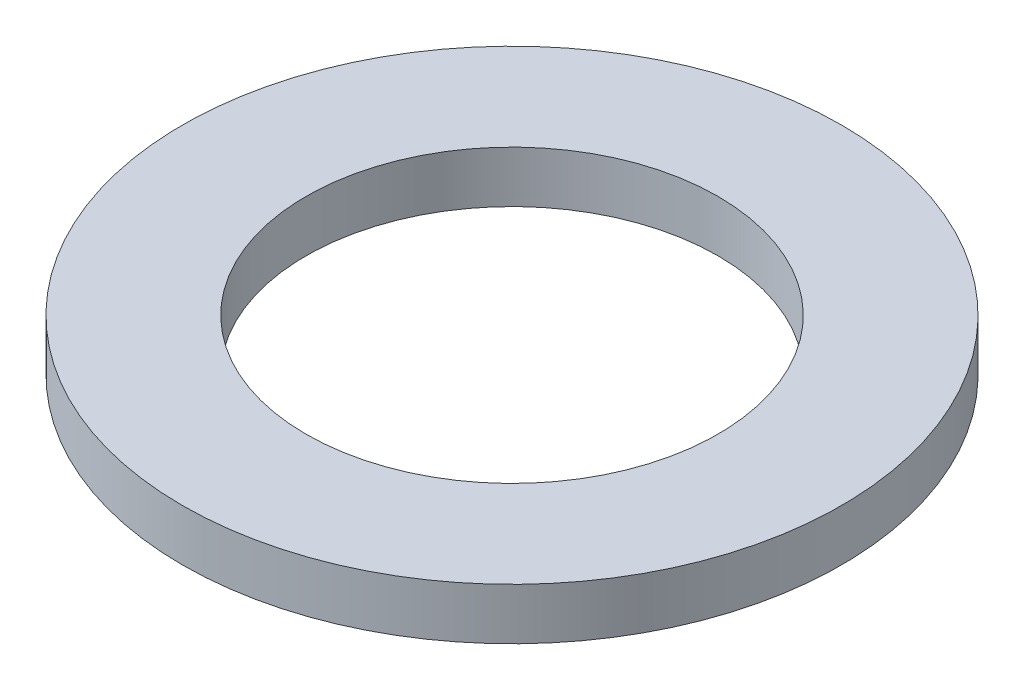
SolidWorks part; units mm, degrees
ref_plane "Front Plane" through (0, 0, 0) normal (0, 0, 1) x (1, 0, 0)
ref_plane "Top Plane" through (0, 0, 0) normal (0, 1, 0) x (1, 0, 0)
ref_plane "Right Plane" through (0, 0, 0) normal (1, 0, 0) x (0, 0, -1)
sketch "Sketch1" plane through (0, 0, 0) normal (0, 1, 0) x (1, 0, 0)
  line L0 (0, 0) -> (0, -10) construction
  line L1 (-1, -11.5) -> (1, -11.5)
  line L2 (-1, -11.5) -> (-1, -14.5)
  line L3 (-1, -14.5) -> (1, -14.5)
  line L4 (1, -11.5) -> (1, -14.5)
  line L5 (-1, -10) -> (1, -10)
  line L6 (-1, -10) -> (-1, -16)
  line L7 (-1, -16) -> (1, -16)
  line L8 (1, -10) -> (1, -16)
  line L9 (-3.0573, -9.5736) -> (-4.3047, -15.4424)
  line L10 (-3.0573, -9.5736) -> (-1.101, -9.9894)
  line L11 (-1.101, -9.9894) -> (-2.3484, -15.8583)
  line L12 (-4.3047, -15.4424) -> (-2.3484, -15.8583)
  line L13 (-3.9929, -13.9752) -> (-2.0366, -14.3911)
  line L14 (-3.3691, -11.0408) -> (-1.4128, -11.4566)
  line L15 (-4.9809, -8.7287) -> (-7.4213, -14.21)
  line L16 (-4.9809, -8.7287) -> (-3.1538, -9.5422)
  line L17 (-3.1538, -9.5422) -> (-5.5942, -15.0235)
  line L18 (-7.4213, -14.21) -> (-5.5942, -15.0235)
  line L19 (-6.8112, -12.8397) -> (-4.9841, -13.6531)
  line L20 (-5.591, -10.099) -> (-3.7639, -10.9125)
  line L21 (-6.6869, -7.5024) -> (-10.2136, -12.3565)
  line L22 (-6.6869, -7.5024) -> (-5.0688, -8.678)
  line L23 (-5.0688, -8.678) -> (-8.5955, -13.5321)
  line L24 (-10.2136, -12.3565) -> (-8.5955, -13.5321)
  line L25 (-9.3319, -11.143) -> (-7.7139, -12.3185)
  line L26 (-7.5685, -8.7159) -> (-5.9505, -9.8915)
  line L27 (-8.1006, -5.9482) -> (-12.5594, -9.9629)
  line L28 (-8.1006, -5.9482) -> (-6.7623, -7.4345)
  line L29 (-6.7623, -7.4345) -> (-11.2212, -11.4492)
  line L30 (-12.5594, -9.9629) -> (-11.2212, -11.4492)
  line L31 (-11.4447, -8.9592) -> (-10.1065, -10.4455)
  line L32 (-9.2153, -6.9519) -> (-7.877, -8.4381)
  line L33 (-9.1603, -4.134) -> (-14.3564, -7.134)
  line L34 (-9.1603, -4.134) -> (-8.1603, -5.866)
  line L35 (-8.1603, -5.866) -> (-13.3564, -8.866)
  line L36 (-14.3564, -7.134) -> (-13.3564, -8.866)
  line L37 (-13.0574, -6.384) -> (-12.0574, -8.116)
  line L38 (-10.4593, -4.884) -> (-9.4593, -6.616)
  line L39 (-9.8196, -2.1391) -> (-15.5259, -3.9932)
  line L40 (-9.8196, -2.1391) -> (-9.2015, -4.0412)
  line L41 (-9.2015, -4.0412) -> (-14.9079, -5.8953)
  line L42 (-15.5259, -3.9932) -> (-14.9079, -5.8953)
  line L43 (-14.0993, -3.5297) -> (-13.4813, -5.4318)
  line L44 (-11.2462, -2.6026) -> (-10.6281, -4.5048)
  line L45 (-10.0497, -0.0508) -> (-16.0169, -0.6779)
  line L46 (-10.0497, -0.0508) -> (-9.8407, -2.0398)
  line L47 (-9.8407, -2.0398) -> (-15.8078, -2.667)
  line L48 (-16.0169, -0.6779) -> (-15.8078, -2.667)
  line L49 (-14.5251, -0.5211) -> (-14.316, -2.5102)
  line L50 (-11.5415, -0.2076) -> (-11.3325, -2.1966)
  line L51 (-9.8407, 2.0398) -> (-15.8078, 2.667)
  line L52 (-9.8407, 2.0398) -> (-10.0497, 0.0508)
  line L53 (-10.0497, 0.0508) -> (-16.0169, 0.6779)
  line L54 (-15.8078, 2.667) -> (-16.0169, 0.6779)
  line L55 (-14.316, 2.5102) -> (-14.5251, 0.5211)
  line L56 (-11.3325, 2.1966) -> (-11.5415, 0.2076)
  line L57 (-9.2015, 4.0412) -> (-14.9079, 5.8953)
  line L58 (-9.2015, 4.0412) -> (-9.8196, 2.1391)
  line L59 (-9.8196, 2.1391) -> (-15.5259, 3.9932)
  line L60 (-14.9079, 5.8953) -> (-15.5259, 3.9932)
  line L61 (-13.4813, 5.4318) -> (-14.0993, 3.5297)
  line L62 (-10.6281, 4.5048) -> (-11.2462, 2.6026)
  line L63 (-8.1603, 5.866) -> (-13.3564, 8.866)
  line L64 (-8.1603, 5.866) -> (-9.1603, 4.134)
  line L65 (-9.1603, 4.134) -> (-14.3564, 7.134)
  line L66 (-13.3564, 8.866) -> (-14.3564, 7.134)
  line L67 (-12.0574, 8.116) -> (-13.0574, 6.384)
  line L68 (-9.4593, 6.616) -> (-10.4593, 4.884)
  line L69 (-6.7623, 7.4345) -> (-11.2212, 11.4492)
  line L70 (-6.7623, 7.4345) -> (-8.1006, 5.9482)
  line L71 (-8.1006, 5.9482) -> (-12.5594, 9.9629)
  line L72 (-11.2212, 11.4492) -> (-12.5594, 9.9629)
  line L73 (-10.1065, 10.4455) -> (-11.4447, 8.9592)
  line L74 (-7.877, 8.4381) -> (-9.2153, 6.9519)
  line L75 (-5.0688, 8.678) -> (-8.5955, 13.5321)
  line L76 (-5.0688, 8.678) -> (-6.6869, 7.5024)
  line L77 (-6.6869, 7.5024) -> (-10.2136, 12.3565)
  line L78 (-8.5955, 13.5321) -> (-10.2136, 12.3565)
  line L79 (-7.7139, 12.3185) -> (-9.3319, 11.143)
  line L80 (-5.9505, 9.8915) -> (-7.5685, 8.7159)
  line L81 (-3.1538, 9.5422) -> (-5.5942, 15.0235)
  line L82 (-3.1538, 9.5422) -> (-4.9809, 8.7287)
  line L83 (-4.9809, 8.7287) -> (-7.4213, 14.21)
  line L84 (-5.5942, 15.0235) -> (-7.4213, 14.21)
  line L85 (-4.9841, 13.6531) -> (-6.8112, 12.8397)
  line L86 (-3.7639, 10.9125) -> (-5.591, 10.099)
  line L87 (-1.101, 9.9894) -> (-2.3484, 15.8583)
  line L88 (-1.101, 9.9894) -> (-3.0573, 9.5736)
  line L89 (-3.0573, 9.5736) -> (-4.3047, 15.4424)
  line L90 (-2.3484, 15.8583) -> (-4.3047, 15.4424)
  line L91 (-2.0366, 14.3911) -> (-3.9929, 13.9752)
  line L92 (-1.4128, 11.4566) -> (-3.3691, 11.0408)
  line L93 (1, 10) -> (1, 16)
  line L94 (1, 10) -> (-1, 10)
  line L95 (-1, 10) -> (-1, 16)
  line L96 (1, 16) -> (-1, 16)
  line L97 (1, 14.5) -> (-1, 14.5)
  line L98 (1, 11.5) -> (-1, 11.5)
  line L99 (3.0573, 9.5736) -> (4.3047, 15.4424)
  line L100 (3.0573, 9.5736) -> (1.101, 9.9894)
  line L101 (1.101, 9.9894) -> (2.3484, 15.8583)
  line L102 (4.3047, 15.4424) -> (2.3484, 15.8583)
  line L103 (3.9929, 13.9752) -> (2.0366, 14.3911)
  line L104 (3.3691, 11.0408) -> (1.4128, 11.4566)
  line L105 (4.9809, 8.7287) -> (7.4213, 14.21)
  line L106 (4.9809, 8.7287) -> (3.1538, 9.5422)
  line L107 (3.1538, 9.5422) -> (5.5942, 15.0235)
  line L108 (7.4213, 14.21) -> (5.5942, 15.0235)
  line L109 (6.8112, 12.8397) -> (4.9841, 13.6531)
  line L110 (5.591, 10.099) -> (3.7639, 10.9125)
  line L111 (6.6869, 7.5024) -> (10.2136, 12.3565)
  line L112 (6.6869, 7.5024) -> (5.0688, 8.678)
  line L113 (5.0688, 8.678) -> (8.5955, 13.5321)
  line L114 (10.2136, 12.3565) -> (8.5955, 13.5321)
  line L115 (9.3319, 11.143) -> (7.7139, 12.3185)
  line L116 (7.5685, 8.7159) -> (5.9505, 9.8915)
  line L117 (8.1006, 5.9482) -> (12.5594, 9.9629)
  line L118 (8.1006, 5.9482) -> (6.7623, 7.4345)
  line L119 (6.7623, 7.4345) -> (11.2212, 11.4492)
  line L120 (12.5594, 9.9629) -> (11.2212, 11.4492)
  line L121 (11.4447, 8.9592) -> (10.1065, 10.4455)
  line L122 (9.2153, 6.9519) -> (7.877, 8.4381)
  line L123 (9.1603, 4.134) -> (14.3564, 7.134)
  line L124 (9.1603, 4.134) -> (8.1603, 5.866)
  line L125 (8.1603, 5.866) -> (13.3564, 8.866)
  line L126 (14.3564, 7.134) -> (13.3564, 8.866)
  line L127 (13.0574, 6.384) -> (12.0574, 8.116)
  line L128 (10.4593, 4.884) -> (9.4593, 6.616)
  line L129 (9.8196, 2.1391) -> (15.5259, 3.9932)
  line L130 (9.8196, 2.1391) -> (9.2015, 4.0412)
  line L131 (9.2015, 4.0412) -> (14.9079, 5.8953)
  line L132 (15.5259, 3.9932) -> (14.9079, 5.8953)
  line L133 (14.0993, 3.5297) -> (13.4813, 5.4318)
  line L134 (11.2462, 2.6026) -> (10.6281, 4.5048)
  line L135 (10.0497, 0.0508) -> (16.0169, 0.6779)
  line L136 (10.0497, 0.0508) -> (9.8407, 2.0398)
  line L137 (9.8407, 2.0398) -> (15.8078, 2.667)
  line L138 (16.0169, 0.6779) -> (15.8078, 2.667)
  line L139 (14.5251, 0.5211) -> (14.316, 2.5102)
  line L140 (11.5415, 0.2076) -> (11.3325, 2.1966)
  line L141 (9.8407, -2.0398) -> (15.8078, -2.667)
  line L142 (9.8407, -2.0398) -> (10.0497, -0.0508)
  line L143 (10.0497, -0.0508) -> (16.0169, -0.6779)
  line L144 (15.8078, -2.667) -> (16.0169, -0.6779)
  line L145 (14.316, -2.5102) -> (14.5251, -0.5211)
  line L146 (11.3325, -2.1966) -> (11.5415, -0.2076)
  line L147 (9.2015, -4.0412) -> (14.9079, -5.8953)
  line L148 (9.2015, -4.0412) -> (9.8196, -2.1391)
  line L149 (9.8196, -2.1391) -> (15.5259, -3.9932)
  line L150 (14.9079, -5.8953) -> (15.5259, -3.9932)
  line L151 (13.4813, -5.4318) -> (14.0993, -3.5297)
  line L152 (10.6281, -4.5048) -> (11.2462, -2.6026)
  line L153 (8.1603, -5.866) -> (13.3564, -8.866)
  line L154 (8.1603, -5.866) -> (9.1603, -4.134)
  line L155 (9.1603, -4.134) -> (14.3564, -7.134)
  line L156 (13.3564, -8.866) -> (14.3564, -7.134)
  line L157 (12.0574, -8.116) -> (13.0574, -6.384)
  line L158 (9.4593, -6.616) -> (10.4593, -4.884)
  line L159 (6.7623, -7.4345) -> (11.2212, -11.4492)
  line L160 (6.7623, -7.4345) -> (8.1006, -5.9482)
  line L161 (8.1006, -5.9482) -> (12.5594, -9.9629)
  line L162 (11.2212, -11.4492) -> (12.5594, -9.9629)
  line L163 (10.1065, -10.4455) -> (11.4447, -8.9592)
  line L164 (7.877, -8.4381) -> (9.2153, -6.9519)
  line L165 (5.0688, -8.678) -> (8.5955, -13.5321)
  line L166 (5.0688, -8.678) -> (6.6869, -7.5024)
  line L167 (6.6869, -7.5024) -> (10.2136, -12.3565)
  line L168 (8.5955, -13.5321) -> (10.2136, -12.3565)
  line L169 (7.7139, -12.3185) -> (9.3319, -11.143)
  line L170 (5.9505, -9.8915) -> (7.5685, -8.7159)
  line L171 (3.1538, -9.5422) -> (5.5942, -15.0235)
  line L172 (3.1538, -9.5422) -> (4.9809, -8.7287)
  line L173 (4.9809, -8.7287) -> (7.4213, -14.21)
  line L174 (5.5942, -15.0235) -> (7.4213, -14.21)
  line L175 (4.9841, -13.6531) -> (6.8112, -12.8397)
  line L176 (3.7639, -10.9125) -> (5.591, -10.099)
  line L177 (1.101, -9.9894) -> (2.3484, -15.8583)
  line L178 (1.101, -9.9894) -> (3.0573, -9.5736)
  line L179 (3.0573, -9.5736) -> (4.3047, -15.4424)
  line L180 (2.3484, -15.8583) -> (4.3047, -15.4424)
  line L181 (2.0366, -14.3911) -> (3.9929, -13.9752)
  line L182 (1.4128, -11.4566) -> (3.3691, -11.0408)
  circle A0 centre (0, 0) radius 10
  circle A1 centre (0, 0) radius 16
  point P11 (0, -10)
  point P248 (0, 0)
  dimension "D1" = 20
  dimension "D2" = 3
  dimension "D3" = 2
  dimension "D4" = 1.5
  dimension "D5" = 1.5
  dimension "D6" = 0
  dimension "D7" = 0
  dimension "D8" = 30
extrude "Boss-Extrude3" add sketch "Sketch1" along normal blind 1
sketch "Sketch2" plane through (0, 1, 0) normal (0, 1, 0) x (1, 0, 0)
  circle A0 centre (0, 0) radius 10 construction
  circle A1 centre (0, 0) radius 16 construction
  circle A2 centre (0, 0) radius 10
  circle A3 centre (0, 0) radius 16
extrude "Boss-Extrude4" add sketch "Sketch2" along normal blind 1.5
